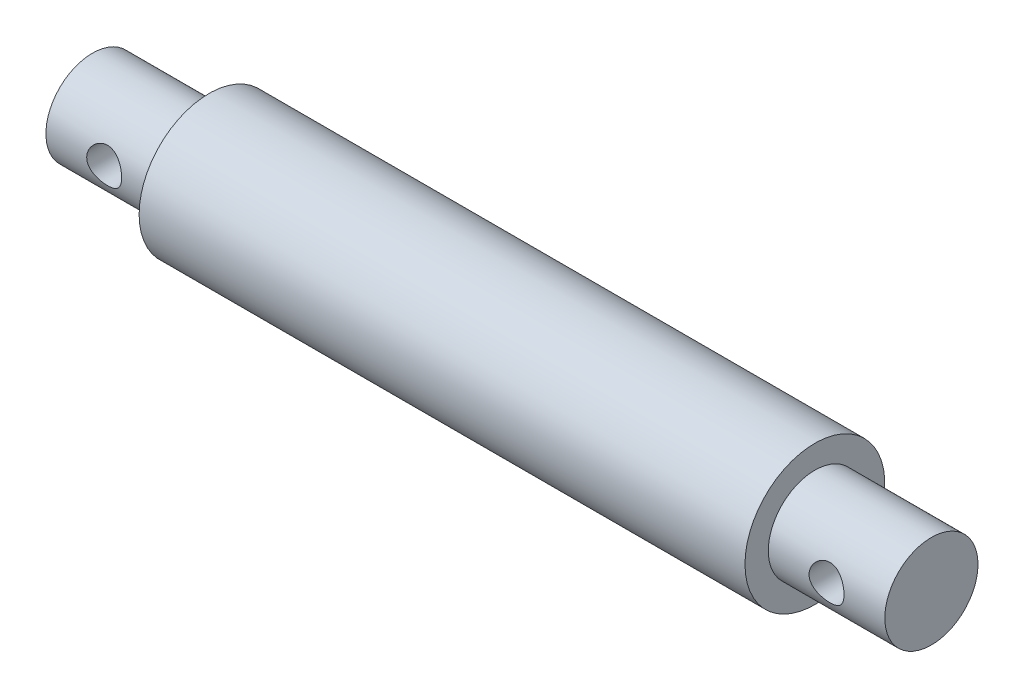
SolidWorks part; units mm, degrees
ref_plane "Front Plane" through (0, 0, 0) normal (0, 0, 1) x (1, 0, 0)
ref_plane "Top Plane" through (0, 0, 0) normal (0, 1, 0) x (1, 0, 0)
ref_plane "Right Plane" through (0, 0, 0) normal (1, 0, 0) x (0, 0, -1)
sketch "Sketch1" plane through (0, 0, 0) normal (1, 0, 0) x (0, 0, -1)
  circle A0 centre (0, 0) radius 2
extrude "Boss-Extrude1" add sketch "Sketch1" along normal blind 5
sketch "Sketch2" plane through (5, 0, 0) normal (1, 0, 0) x (0, 0, -1)
  circle A0 centre (0, 0) radius 3
extrude "Boss-Extrude2" add sketch "Sketch2" along normal blind 26
sketch "Sketch3" plane through (31, 0, 0) normal (1, 0, 0) x (0, 0, -1)
  circle A0 centre (0, 0) radius 2
extrude "Boss-Extrude3" add sketch "Sketch3" along normal blind 5
sketch "Sketch4" plane through (0, 0, 0) normal (0, 0, 1) x (1, 0, 0)
  circle A0 centre (33.5, 0) radius 0.75
  circle A1 centre (2.5, 0) radius 0.75
  dimension "D1" = 2
extrude "Cut-Extrude1" cut sketch "Sketch4" against normal mid plane 5
